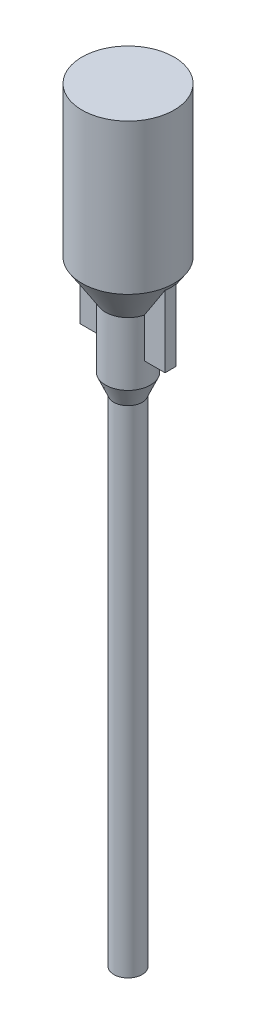
SolidWorks part; units mm, degrees
ref_plane "Front Plane" through (0, 0, 0) normal (0, 0, 1) x (1, 0, 0)
ref_plane "Top Plane" through (0, 0, 0) normal (0, 1, 0) x (1, 0, 0)
ref_plane "Right Plane" through (0, 0, 0) normal (1, 0, 0) x (0, 0, -1)
sketch "Sketch1" plane through (0, 0, 0) normal (0, 0, 1) x (1, 0, 0)
  line L0 (1, 35) -> (1.585, 36.35)
  line L1 (0, 0) -> (1, 0)
  line L2 (0, 0) -> (0, 35)
  line L3 (0, 35) -> (1, 35)
  line L4 (1, 0) -> (1, 35)
  line L5 (0, 35) -> (1.585, 35)
  line L6 (0, 35) -> (0, 40.8)
  line L7 (0, 40.8) -> (1.585, 40.8)
  line L8 (1.585, 35) -> (1.585, 40.8)
  line L9 (0, 40.8) -> (3.25, 40.8)
  line L10 (0, 40.8) -> (0, 54)
  line L11 (0, 54) -> (3.25, 54)
  line L12 (3.25, 40.8) -> (3.25, 54)
  line L13 (1.585, 40.8) -> (3.25, 43.4)
  dimension "D1" = 1
  dimension "D2" = 35
  dimension "D3" = 1.585
  dimension "D4" = 5.8
  dimension "D5" = 13.2
  dimension "D6" = 3.25
  dimension "D7" = 1.35
  dimension "D8" = 2.6
revolve "Revolve1" add sketch "Sketch1" angle 360 about L10
shell "Shell1" thickness 0.15
sketch "Sketch2" plane through (0, 54, 0) normal (0, 1, 0) x (1, 0, 0)
  line L1 (3, -0.385) -> (-3, -0.385)
  line L2 (3, -0.385) -> (3, 0.385)
  line L3 (3, 0.385) -> (-3, 0.385)
  line L4 (-3, -0.385) -> (-3, 0.385)
  line L5 (3, -0.385) -> (-3, 0.385) construction
  line L6 (3, 0.385) -> (-3, -0.385) construction
  point P0 (0, 0)
  dimension "D1" = 0.77
  dimension "D2" = 6
extrude "Boss-Extrude1" add sketch "Sketch2" against normal blind 16
